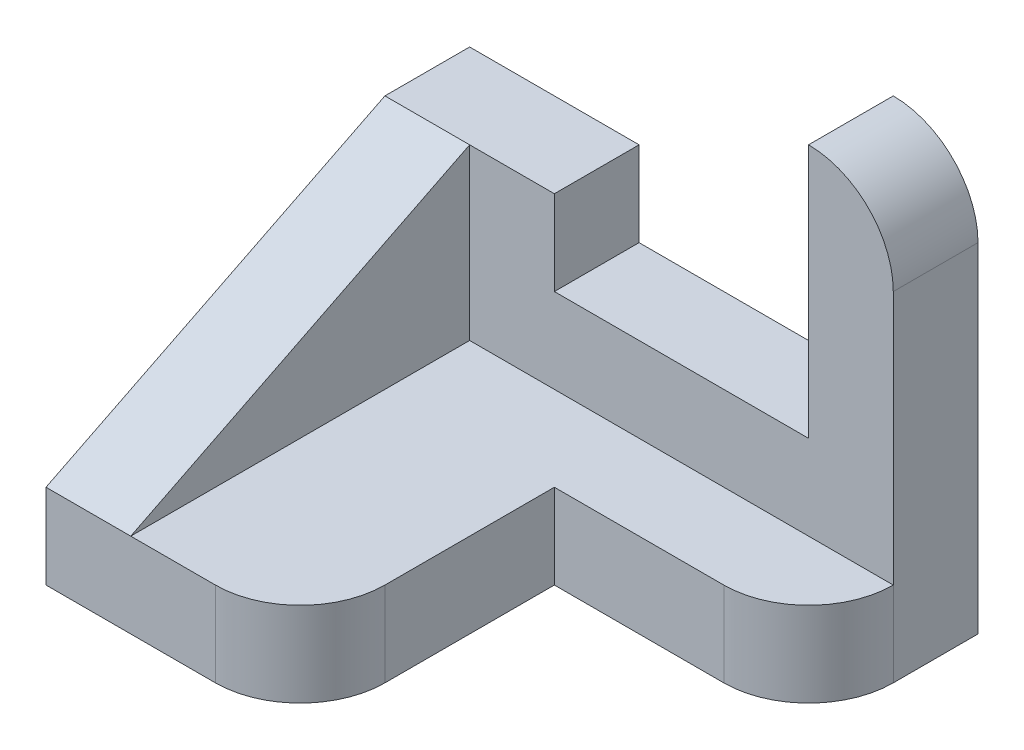
SolidWorks part; units mm, degrees
ref_plane "Front Plane" through (0, 0, 0) normal (0, 0, 1) x (1, 0, 0)
ref_plane "Top Plane" through (0, 0, 0) normal (0, 1, 0) x (1, 0, 0)
ref_plane "Right Plane" through (0, 0, 0) normal (1, 0, 0) x (0, 0, -1)
sketch "Sketch1" plane through (0, 0, 0) normal (0, 1, 0) x (1, 0, 0)
  line L0 (20, 5) -> (0, 5)
  line L1 (-30, 25) -> (30, 25)
  line L2 (-30, 25) -> (-30, -25)
  line L3 (-30, -25) -> (-10, -25)
  line L4 (30, 25) -> (30, 15)
  line L7 (0, 5) -> (0, -15)
  arc A0 (-10, -25) -> (0, -15) centre (-10, -15) ccw
  arc A1 (20, 5) -> (30, 15) centre (20, 15) ccw
  point P0 (0, 0)
  dimension "D5" = 10
  dimension "D1" = 50
  dimension "D2" = 60
  dimension "D3" = 20
  dimension "D4" = 30
extrude "Boss-Extrude1" add sketch "Sketch1" along normal blind 10
sketch "Sketch2" plane through (0, 0, -25) normal (0, 0, -1) x (-1, 0, 0)
  line L0 (-30, 10) -> (-30, 40)
  line L3 (-20, 20) -> (10, 20)
  line L4 (10, 20) -> (10, 30)
  line L5 (10, 30) -> (30, 30)
  line L6 (30, 30) -> (30, 10)
  line L7 (-30, 10) -> (30, 10) construction
  line L8 (-30, 10) -> (30, 10)
  line L10 (-20, 20) -> (-20, 50)
  arc A0 (-30, 40) -> (-20, 50) centre (-20, 40) cw
  dimension "D2" = 10
  dimension "D1" = 30
  dimension "D4" = 20
  dimension "D5" = 10
extrude "Boss-Extrude2" add sketch "Sketch2" against normal blind 10 contours L6 L8 L0 A0 L10 L3 L4 L5
sketch "Sketch3" plane through (-30, 0, 0) normal (-1, 0, 0) x (0, 0, 1)
  line L0 (-15, 30) -> (25, 10)
  line L1 (25, 10) -> (25, 0) construction
  line L2 (-15, 10) -> (25, 10) construction
  line L3 (-15, 30) -> (-15, 10)
  line L4 (-15, 10) -> (25, 10)
extrude "Boss-Extrude3" add sketch "Sketch3" against normal blind 10
